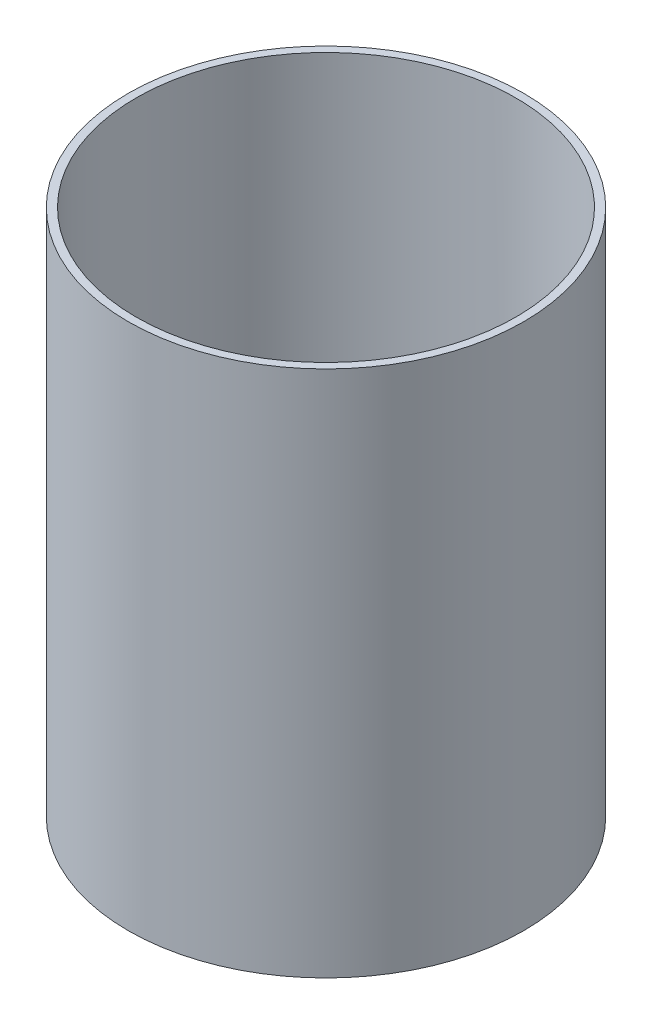
SolidWorks part; units mm, degrees
ref_plane "Front Plane" through (0, 0, 0) normal (0, 0, 1) x (1, 0, 0)
ref_plane "Top Plane" through (0, 0, 0) normal (0, 1, 0) x (1, 0, 0)
ref_plane "Right Plane" through (0, 0, 0) normal (1, 0, 0) x (0, 0, -1)
sketch "Sketch1" plane through (0, 0, 0) normal (0, 1, 0) x (1, 0, 0)
  circle A0 centre (0, 0) radius 36.576
  circle A1 centre (0, 0) radius 38.1
  dimension "D1" = 73.152
  dimension "D2" = 76.2
extrude "Boss-Extrude1" add sketch "Sketch1" along normal mid plane 101.6
sketch "Sketch2" plane through (0, 0, 0) normal (1, 0, 0) x (0, 0, -1)
  line L0 (-38.1, -50.8) -> (38.1, -50.8) construction
  line L1 (38.1, 50.8) -> (-38.1, 50.8) construction
  line L2 (-38.1, -50.8) -> (38.1, -50.8) construction
  line L3 (38.1, 50.8) -> (-38.1, 50.8) construction
  circle A0 centre (0, 0) radius 6.35
  dimension "D1" = 12.7
extrude "Cut-Extrude1" cut sketch "Sketch2" against normal through all
sketch "Sketch3" plane through (0, 0, 0) normal (0, 0, 1) x (1, 0, 0)
  circle A0 centre (0, 0) radius 6.35
  dimension "D1" = 12.7
extrude "Cut-Extrude2" cut sketch "Sketch3" against normal through all
equation "\"airframeInnerDiameter\"=3"
equation "\"outerDiameter\"=3.124"
equation "\"recoveryBayInnerDiameter\"=2.88"
equation "\"recoveryBayLength\"=4"
equation "\"recoveryCouplerOuter\"=\"airframeInnerDiameter\""
equation "\"D1@Sketch1\"=\"recoveryBayInnerDiameter\""
equation "\"D2@Sketch1\"=\"recoveryCouplerOuter\""
equation "\"D1@Boss-Extrude1\"=\"recoveryBayLength\""
